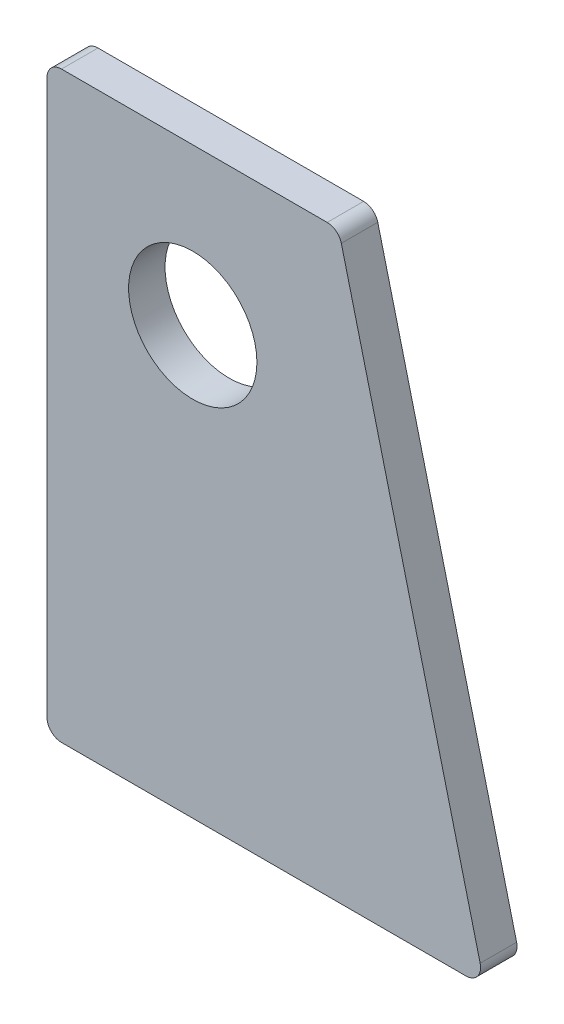
SolidWorks part; units mm, degrees
ref_plane "Front Plane" through (0, 0, 0) normal (0, 0, 1) x (1, 0, 0)
ref_plane "Top Plane" through (0, 0, 0) normal (0, 1, 0) x (1, 0, 0)
ref_plane "Right Plane" through (0, 0, 0) normal (1, 0, 0) x (0, 0, -1)
sketch "Sketch1" plane through (0, 0, 0) normal (0, 0, 1) x (1, 0, 0)
  line L0 (50.8, -101.6) -> (76.2562, -101.6)
  line L1 (0, 0) -> (50.8, 0)
  line L2 (0, 0) -> (0, -101.6)
  line L3 (0, -101.6) -> (50.8, -101.6)
  line L4 (50.8, 0) -> (50.8, -101.6)
  line L5 (76.2562, -101.6) -> (50.8, 0)
  circle A0 centre (25.4, -27.2197) radius 11.176
  dimension "D3" = 22.352
  dimension "D1" = 50.8
  dimension "D2" = 101.6
extrude "Boss-Extrude1" add sketch "Sketch1" along normal blind 6.35 contours L4 L1 L2 L3 A0 | L0 L5 L4
fillet "Fillet1" radius 2.54 4 edges at (0, -101.6, 3.175) (76.2562, -101.6, 3.175) (0, 0, 3.175) (50.8, 0, 3.175)
